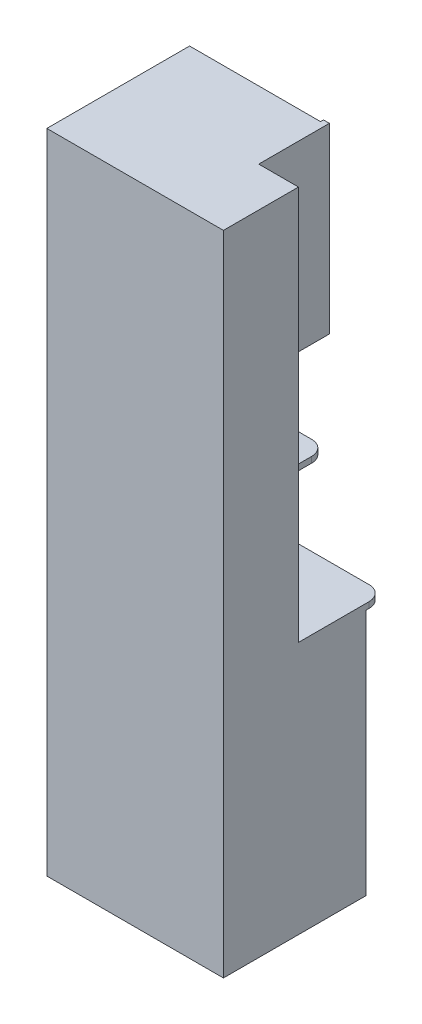
SolidWorks part; units mm, degrees
ref_plane "정면" through (0, 0, 0) normal (0, 0, 1) x (1, 0, 0)
ref_plane "윗면" through (0, 0, 0) normal (0, 1, 0) x (1, 0, 0)
ref_plane "우측면" through (0, 0, 0) normal (1, 0, 0) x (0, 0, -1)
sketch "스케치1" plane through (0, 0, 0) normal (0, 0, 1) x (1, 0, 0)
  line L1 (300, 1100) -> (-300, 1100)
  line L2 (300, 1100) -> (300, -1100)
  line L3 (300, -1100) -> (-300, -1100)
  line L4 (-300, 1100) -> (-300, -1100)
  line L5 (300, 1100) -> (-300, -1100) construction
  line L6 (300, -1100) -> (-300, 1100) construction
  point P0 (0, 0)
  dimension "D1" = 600
  dimension "D2" = 2200
extrude "보스-돌출1" add sketch "스케치1" against normal blind 485
sketch "스케치2" plane through (300, 0, 0) normal (1, 0, 0) x (0, 0, -1)
  line L0 (485, -1100) -> (0, -1100) construction
  line L1 (485, 1100) -> (255, 1100)
  line L2 (485, 1100) -> (485, -260)
  line L3 (485, -260) -> (255, -260)
  line L4 (255, 1100) -> (255, -260)
  dimension "D1" = 230
  dimension "D2" = 840
extrude "컷-돌출1" cut sketch "스케치2" against normal blind 135
sketch "스케치3" plane through (165, 0, 0) normal (1, 0, 0) x (0, 0, -1)
  line L0 (255, 1100) -> (255, -260) construction
  line L1 (485, -260) -> (255, -260)
  line L2 (485, -260) -> (485, 130)
  line L3 (485, 130) -> (255, 130)
  line L4 (255, -260) -> (255, 130)
  dimension "D1" = 390
extrude "컷-돌출2" cut sketch "스케치3" against normal blind 445
sketch "스케치4" plane through (165, 0, 0) normal (1, 0, 0) x (0, 0, -1)
  line L0 (485, 130) -> (485, 1100) construction
  line L1 (485, 490) -> (255, 490)
  line L2 (485, 490) -> (485, 150)
  line L3 (485, 150) -> (255, 150)
  line L4 (255, 490) -> (255, 150)
  line L5 (255, 1100) -> (255, 130) construction
  line L6 (485, 130) -> (255, 130) construction
  dimension "D1" = 340
  dimension "D2" = 20
extrude "컷-돌출3" cut sketch "스케치4" against normal blind 445
sketch "스케치5" plane through (0, -260, 0) normal (0, 1, 0) x (1, 0, 0)
  line L1 (-280, 255) -> (300, 255)
  line L2 (-280, 255) -> (-280, 545)
  line L3 (-280, 545) -> (300, 545)
  line L4 (300, 255) -> (300, 545)
  dimension "D1" = 290
  dimension "D2" = 580
extrude "보스-돌출2" add sketch "스케치5" along normal blind 20
fillet "필렛1" radius 50 1 edges at (300, -250, -545)
sketch "스케치6" plane through (165, 0, 0) normal (1, 0, 0) x (0, 0, -1)
  line L2 (485, 1100) -> (255, 1100)
  line L3 (485, 1100) -> (485, 490)
  line L4 (485, 490) -> (255, 490)
  line L5 (255, 1100) -> (255, 490)
extrude "컷-돌출4" cut sketch "스케치6" against normal blind 20
sketch "스케치7" plane through (145, 0, 0) normal (1, 0, 0) x (0, 0, -1)
  line L1 (255, 1100) -> (495, 1100)
  line L2 (255, 1100) -> (255, 480)
  line L3 (255, 480) -> (495, 480)
  line L4 (495, 1100) -> (495, 480)
  dimension "D1" = 620
  dimension "D2" = 240
extrude "보스-돌출3" add sketch "스케치7" along normal blind 20
fillet "필렛2" radius 50 1 edges at (-280, -250, -545)
fillet "필렛3" radius 50 1 edges at (165, 140, -485)
